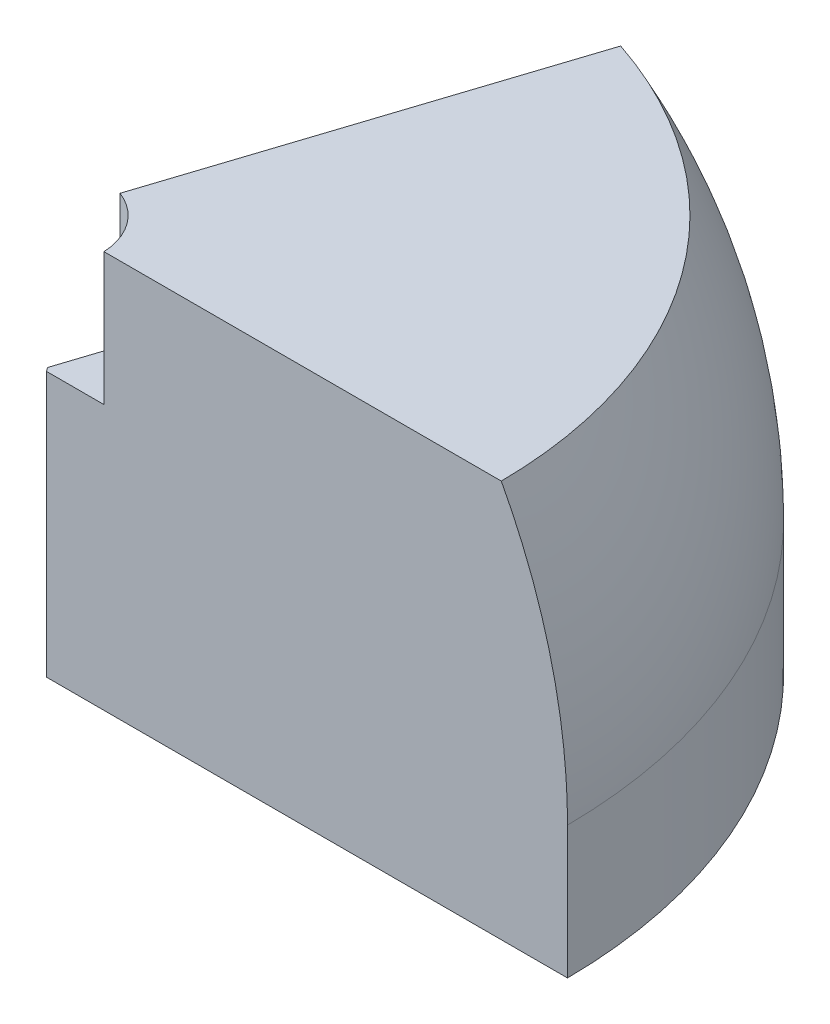
SolidWorks part; units mm, degrees
material "Polyurethane Foam Rigid"
ref_plane "Front Plane" through (0, 0, 0) normal (0, 0, 1) x (1, 0, 0)
ref_plane "Top Plane" through (0, 0, 0) normal (0, 1, 0) x (1, 0, 0)
ref_plane "Right Plane" through (0, 0, 0) normal (1, 0, 0) x (0, 0, -1)
sketch "Sketch1" plane through (0, 0, 0) normal (0, 0, 1) x (1, 0, 0)
  line L0 (0, 0) -> (0, 76.2)
  line L1 (0, 76.2) -> (88.9, 76.2)
  line L2 (0, 0) -> (101.6, 0)
  line L3 (101.6, 0) -> (101.6, 25.4)
  arc A0 (88.9, 76.2) -> (101.6, 25.4) centre (-6.35, 25.4) cw
  dimension "D1" = 101.6
  dimension "D2" = 76.2
  dimension "D3" = 12.7
  dimension "D4" = 25.4
revolve "Revolve1" add sketch "Sketch1" angle 72 about L0
sketch "Sketch3" plane through (0, 0, 0) normal (-0.9511, 0, -0.309) x (-0.309, 0, 0.9511)
  line L7 (0, 76.2) -> (-88.9, 76.2)
  line L8 (-101.6, 25.4) -> (-101.6, 0)
  line L9 (-101.6, 0) -> (0, 0)
  line L10 (0, 0) -> (0, 76.2)
  line L13 (0, 76.2) -> (-88.9, 76.2)
  line L14 (-101.6, 25.4) -> (-101.6, 0)
  line L15 (-101.6, 0) -> (0, 0)
  line L16 (0, 0) -> (0, 76.2)
  arc A1 (-88.9, 76.2) -> (-101.6, 25.4) centre (6.35, 25.4) ccw
  arc A2 (-88.9, 76.2) -> (-101.6, 25.4) centre (6.35, 25.4) ccw
  dimension "D1" = 0
extrude "Cut-Extrude2" cut sketch "Sketch3" against normal blind 0.635
sketch "Sketch4" plane through (0, 0, 0) normal (0, 0, 1) x (1, 0, 0)
  line L6 (0.6677, 76.2) -> (0.6677, 0)
  line L7 (0.6677, 0) -> (101.6, 0)
  line L8 (101.6, 0) -> (101.6, 25.4)
  line L9 (88.9, 76.2) -> (0.6677, 76.2)
  line L12 (0.6677, 76.2) -> (0.6677, 0)
  line L13 (0.6677, 0) -> (101.6, 0)
  line L14 (101.6, 0) -> (101.6, 25.4)
  line L15 (88.9, 76.2) -> (0.6677, 76.2)
  arc A1 (101.6, 25.4) -> (88.9, 76.2) centre (-6.35, 25.4) ccw
  arc A2 (101.6, 25.4) -> (88.9, 76.2) centre (-6.35, 25.4) ccw
  dimension "D1" = 0
extrude "Cut-Extrude3" cut sketch "Sketch4" against normal blind 0.635
sketch "Sketch2" plane through (0, 76.2, 0) normal (0, 1, 0) x (1, 0, 0)
  circle A0 centre (0, 0) radius 12.7
  dimension "D1" = 25.4
extrude "Cut-Extrude1" cut sketch "Sketch2" against normal blind 25.4
sketch "Sketch5" plane through (0, 50.8, 0) normal (0, 1, 0) x (1, 0, 0)
  line L0 (1.6589, 0.635) -> (1.1166, 1.3815)
  line L1 (12.6841, 0.635) -> (0.874, 0.635) construction
  line L2 (0.874, 0.635) -> (4.5235, 11.8671) construction
  line L3 (1.1166, 1.3815) -> (0.874, 0.635)
  line L4 (0.874, 0.635) -> (1.6589, 0.635)
  dimension "D1" = 0.635
extrude "Cut-Extrude4" cut sketch "Sketch5" against normal up to next
